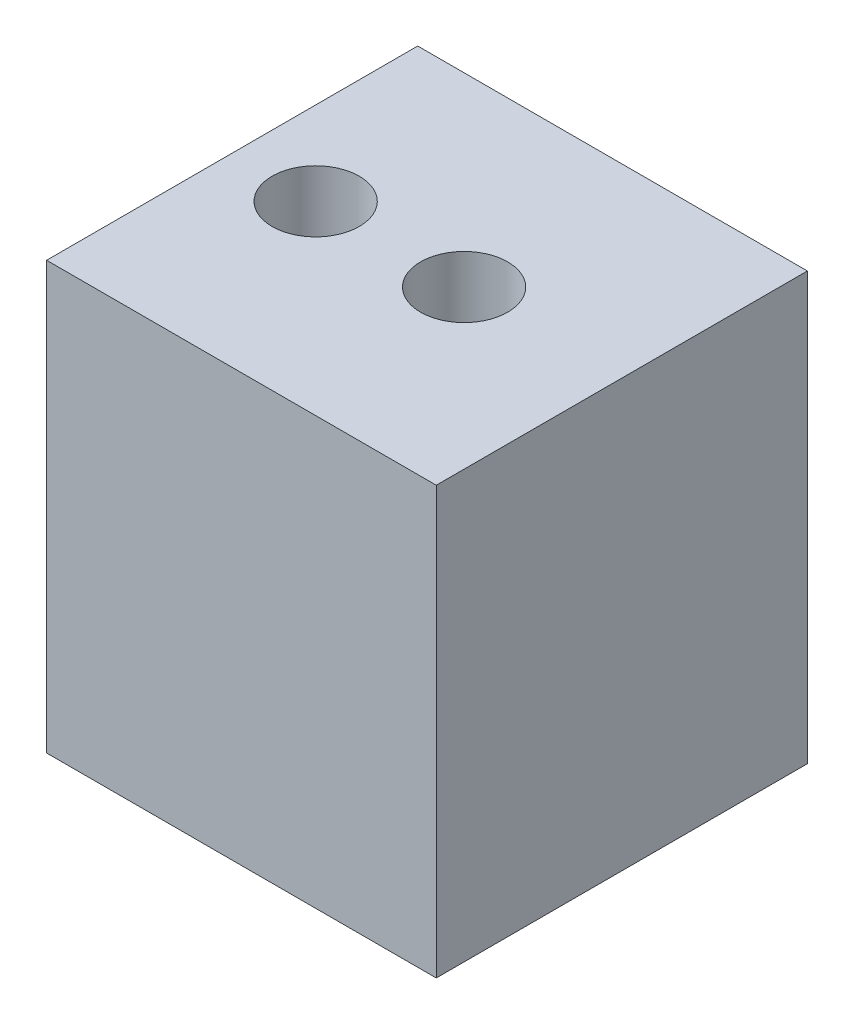
SolidWorks part; units mm, degrees
ref_plane "Front Plane" through (0, 0, 0) normal (0, 0, 1) x (1, 0, 0)
ref_plane "Top Plane" through (0, 0, 0) normal (0, 1, 0) x (1, 0, 0)
ref_plane "Right Plane" through (0, 0, 0) normal (1, 0, 0) x (0, 0, -1)
sketch "Sketch1" plane through (0, 0, 0) normal (0, 1, 0) x (1, 0, 0)
  line L1 (-10.5, -10) -> (10.5, -10)
  line L2 (-10.5, -10) -> (-10.5, 10)
  line L3 (-10.5, 10) -> (10.5, 10)
  line L4 (10.5, -10) -> (10.5, 10)
  line L5 (-10.5, -10) -> (10.5, 10) construction
  line L6 (-10.5, 10) -> (10.5, -10) construction
  circle A0 centre (-6, 0) radius 2.35
  circle A1 centre (2, 0) radius 2.35
  point P0 (0, 0)
  dimension "D3" = 4.7
  dimension "D5" = 4.7
  dimension "D1" = 20
  dimension "D2" = 21
  dimension "D4" = 8
  dimension "D6" = 16.5
extrude "Boss-Extrude1" add sketch "Sketch1" along normal blind 23
